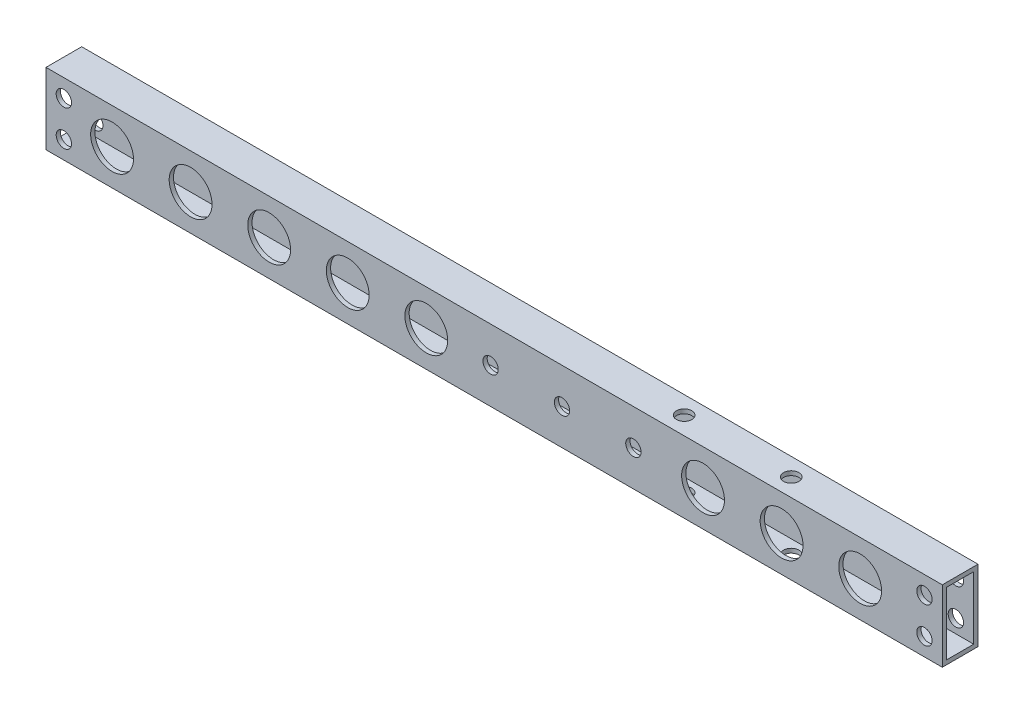
SolidWorks part; units mm, degrees
material "5052-H34"
ref_plane "正面" through (0, 0, 0) normal (0, 0, 1) x (1, 0, 0)
ref_plane "平面" through (0, 0, 0) normal (0, 1, 0) x (1, 0, 0)
ref_plane "右側面" through (0, 0, 0) normal (1, 0, 0) x (0, 0, -1)
sketch "ｽｹｯﾁ1" plane through (0, 0, 0) normal (1, 0, 0) x (0, 0, -1)
  line L1 (-5, 10) -> (5, 10)
  line L2 (-5, 10) -> (-5, -10)
  line L3 (-5, -10) -> (5, -10)
  line L4 (5, 10) -> (5, -10)
  line L5 (-5, 10) -> (5, -10) construction
  line L6 (-5, -10) -> (5, 10) construction
  point P0 (0, 0)
  dimension "D1" = 10
  dimension "D2" = 20
extrude "押し出し-薄板1" add sketch "ｽｹｯﾁ1" along normal blind 350 thin
sketch "ｽｹｯﾁ2" plane through (0, 0, 5) normal (0, 0, 1) x (1, 0, 0)
  line L0 (125.5, 10) -> (125.5, -10) construction
  line L3 (164.5, 0) -> (124.5, 0) construction
  line L4 (0, 0) -> (5, 0) construction
  line L6 (350, 10) -> (0, 10) construction
  line L7 (350, -10) -> (0, -10) construction
  line L8 (0, 10) -> (0, -10) construction
  line L9 (5, 0) -> (5, 5) construction
  line L10 (350, 0) -> (0, 0) construction
  line L11 (350, 10) -> (350, -10) construction
  circle A2 centre (246, 5) radius 2.15
  circle A3 centre (246, -5) radius 2.15
  circle A4 centre (5, -5) radius 2.15
  circle A5 centre (5, 5) radius 2.15
  circle A7 centre (164.5, 0) radius 2.15
  circle A8 centre (144.5, 0) radius 2.15
  circle A9 centre (124.5, 0) radius 2.15
  circle A10 centre (330, 0) radius 6
  circle A11 centre (308, 0) radius 6
  circle A12 centre (286, 0) radius 6
  circle A13 centre (264, 0) radius 6
  circle A14 centre (228, 0) radius 6
  circle A15 centre (206, 0) radius 6
  circle A16 centre (184, 0) radius 6
  circle A17 centre (106.5, 0) radius 6
  circle A18 centre (84.5, 0) radius 6
  circle A19 centre (62.5, 0) radius 6
  circle A20 centre (40.5, 0) radius 6
  circle A21 centre (18.5, 0) radius 6
  point P8 (144.5, 0)
  dimension "D1" = 40
  dimension "D3" = 4.3
  dimension "D6" = 4.3
  dimension "D2" = 139.5
  dimension "D7" = 241
  dimension "D10" = 12
  dimension "D4" = 10
  dimension "D5" = 5
  dimension "D8" = 125.5
  dimension "D9" = 20
  dimension "D11" = 22
  dimension "D12" = 22
  dimension "D13" = 22
  dimension "D14" = 22
  dimension "D15" = 18
  dimension "D16" = 22
  dimension "D17" = 18
  dimension "D18" = 22
  dimension "D19" = 22
  dimension "D20" = 22
  dimension "D21" = 22
extrude "ｶｯﾄ - 押し出し1" cut sketch "ｽｹｯﾁ2" against normal through all
sketch "ｽｹｯﾁ3" plane through (0, 10, 0) normal (0, 1, 0) x (1, 0, 0)
  line L0 (350, 0) -> (343.25, 0) construction
  line L1 (350, 5) -> (350, -5) construction
  line L2 (173.7, 0) -> (203.7, 0) construction
  circle A0 centre (343.25, 0) radius 3.175
  circle A1 centre (173.7, 0) radius 2.15
  circle A2 centre (203.7, 0) radius 2.15
  point P10 (188.7, 0)
  dimension "D1" = 6.35
  dimension "D3" = 4.3
  dimension "D2" = 6.75
  dimension "D4" = 30
  dimension "D5" = 161.3
extrude "ｶｯﾄ - 押し出し2" cut sketch "ｽｹｯﾁ3" against normal through all
sketch "ｽｹｯﾁ4" plane through (0, 0, 5) normal (0, 0, 1) x (1, 0, 0)
  line L0 (350, -10) -> (0, -10) construction
  line L1 (350, 10) -> (251, 10)
  line L2 (350, 10) -> (350, -10)
  line L3 (350, -10) -> (251, -10)
  line L4 (251, 10) -> (251, -10)
  circle A0 centre (246, -5) radius 2.15 construction
  dimension "D1" = 5
extrude "ｶｯﾄ - 押し出し3" cut sketch "ｽｹｯﾁ4" against normal up to surface (10 mm away) up to face at (336, 0, -5)
